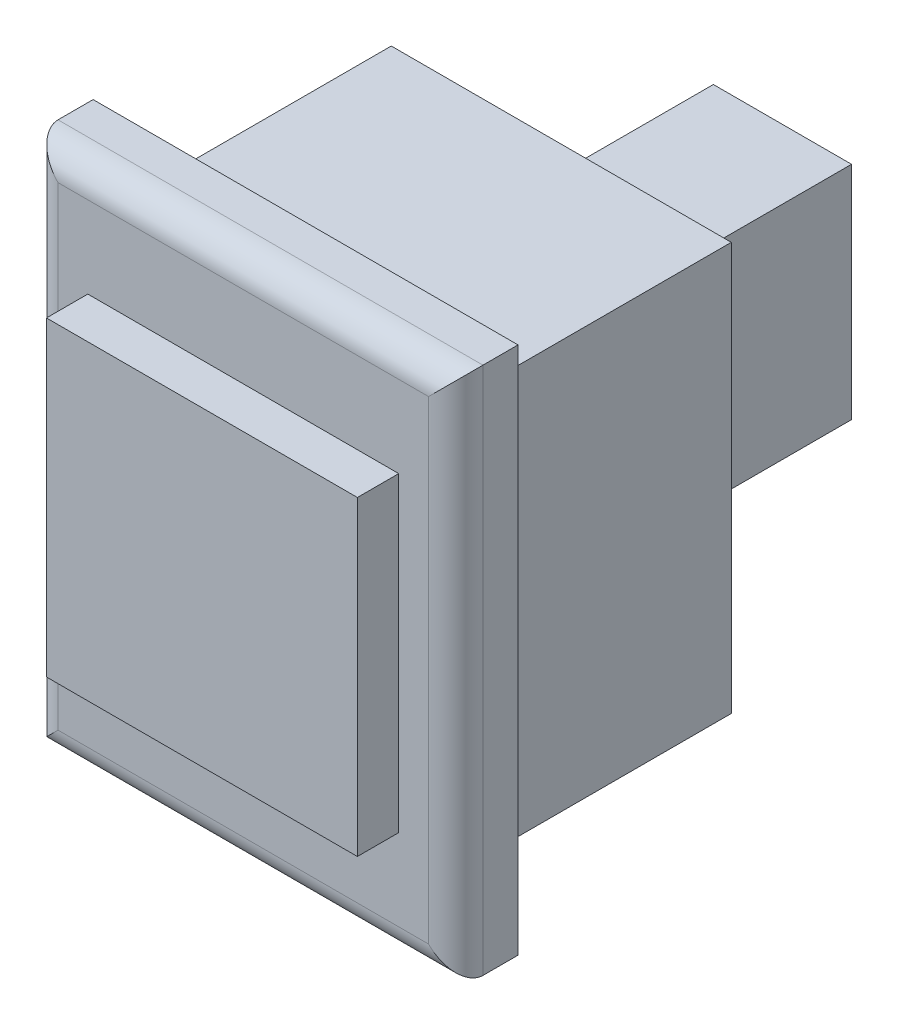
SolidWorks part; units mm, degrees
ref_plane "Front Plane" through (0, 0, 0) normal (0, 0, 1) x (1, 0, 0)
ref_plane "Top Plane" through (0, 0, 0) normal (0, 1, 0) x (1, 0, 0)
ref_plane "Right Plane" through (0, 0, 0) normal (1, 0, 0) x (0, 0, -1)
sketch "Sketch1" plane through (0, 0, 0) normal (0, 0, 1) x (1, 0, 0)
  line L1 (-7.81, 9.715) -> (7.81, 9.715)
  line L2 (-7.81, 9.715) -> (-7.81, -9.715)
  line L3 (-7.81, -9.715) -> (7.81, -9.715)
  line L4 (7.81, 9.715) -> (7.81, -9.715)
  line L5 (-7.81, 9.715) -> (7.81, -9.715) construction
  line L6 (-7.81, -9.715) -> (7.81, 9.715) construction
  point P0 (0, 0)
  dimension "D1" = 19.43
  dimension "D2" = 15.62
extrude "Boss-Extrude1" add sketch "Sketch1" along normal blind 2.29
sketch "Sketch2" plane through (0, 0, 0) normal (0, 0, -1) x (-1, 0, 0)
  line L1 (5.715, 5.715) -> (-5.715, 5.715)
  line L2 (5.715, 5.715) -> (5.715, -5.715)
  line L3 (5.715, -5.715) -> (-5.715, -5.715)
  line L4 (-5.715, 5.715) -> (-5.715, -5.715)
  line L5 (5.715, 5.715) -> (-5.715, -5.715) construction
  line L6 (5.715, -5.715) -> (-5.715, 5.715) construction
  point P0 (0, 0)
  dimension "D1" = 11.43
  dimension "D2" = 11.43
extrude "Boss-Extrude2" add sketch "Sketch2" against normal blind 3.81
fillet "Fillet1" radius 1 4 edges at (-7.81, 0, 2.29) (0, -9.715, 2.29) (7.81, 0, 2.29) (0, 9.715, 2.29)
sketch "Sketch3" plane through (0, 0, 0) normal (0, 0, -1) x (-1, 0, 0)
  line L1 (-6.25, 7.5) -> (6.25, 7.5)
  line L2 (-6.25, 7.5) -> (-6.25, -7.5)
  line L3 (-6.25, -7.5) -> (6.25, -7.5)
  line L4 (6.25, 7.5) -> (6.25, -7.5)
  line L5 (-6.25, 7.5) -> (6.25, -7.5) construction
  line L6 (-6.25, -7.5) -> (6.25, 7.5) construction
  point P0 (0, 0)
  dimension "D1" = 12.5
  dimension "D2" = 15
extrude "Boss-Extrude3" add sketch "Sketch3" along normal blind 9.4
sketch "Sketch4" plane through (0, 0, -9.4) normal (0, 0, -1) x (-1, 0, 0)
  line L1 (-2.54, 4.065) -> (2.54, 4.065)
  line L2 (-2.54, 4.065) -> (-2.54, -4.065)
  line L3 (-2.54, -4.065) -> (2.54, -4.065)
  line L4 (2.54, 4.065) -> (2.54, -4.065)
  line L5 (-2.54, 4.065) -> (2.54, -4.065) construction
  line L6 (-2.54, -4.065) -> (2.54, 4.065) construction
  point P0 (0, 0)
  dimension "D1" = 8.13
  dimension "D2" = 5.08
extrude "Boss-Extrude4" add sketch "Sketch4" along normal blind 8.13
